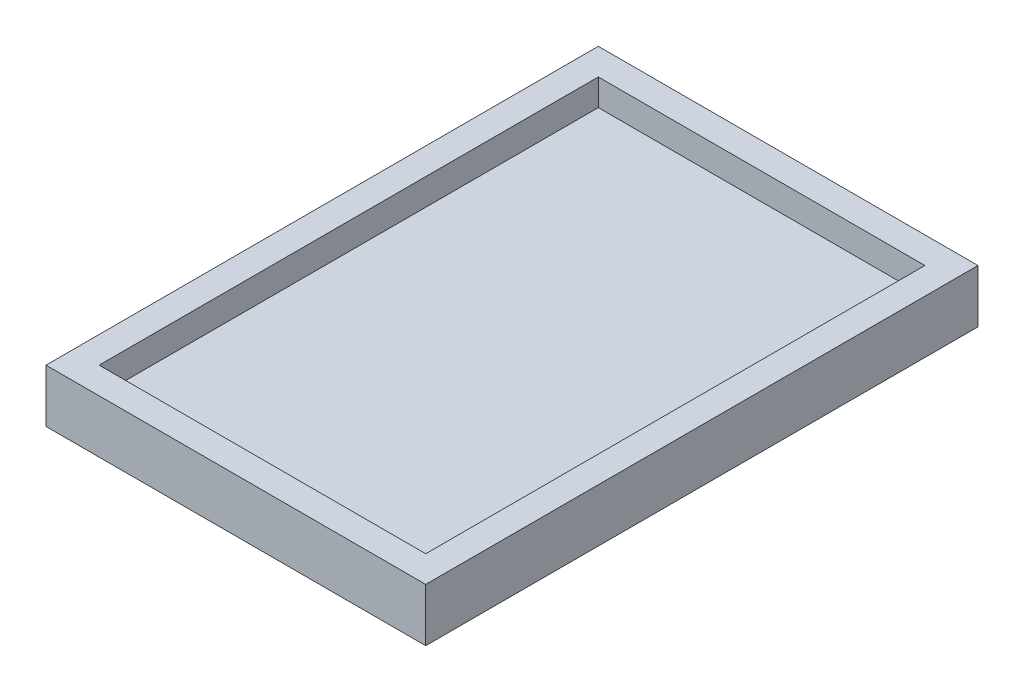
SolidWorks part; units mm, degrees
ref_plane "Front Plane" through (0, 0, 0) normal (0, 0, 1) x (1, 0, 0)
ref_plane "Top Plane" through (0, 0, 0) normal (0, 1, 0) x (1, 0, 0)
ref_plane "Right Plane" through (0, 0, 0) normal (1, 0, 0) x (0, 0, -1)
sketch "Sketch1" plane through (0, 0, 0) normal (0, 1, 0) x (1, 0, 0)
  line L1 (-61.5, -94) -> (61.5, -94)
  line L2 (-61.5, -94) -> (-61.5, 94)
  line L3 (-61.5, 94) -> (61.5, 94)
  line L4 (61.5, -94) -> (61.5, 94)
  line L5 (-61.5, -94) -> (61.5, 94) construction
  line L6 (-61.5, 94) -> (61.5, -94) construction
  point P0 (0, 0)
  dimension "D1" = 123
  dimension "D2" = 188
extrude "Boss-Extrude1" add sketch "Sketch1" along normal blind 10
shell "Shell1" thickness 10
